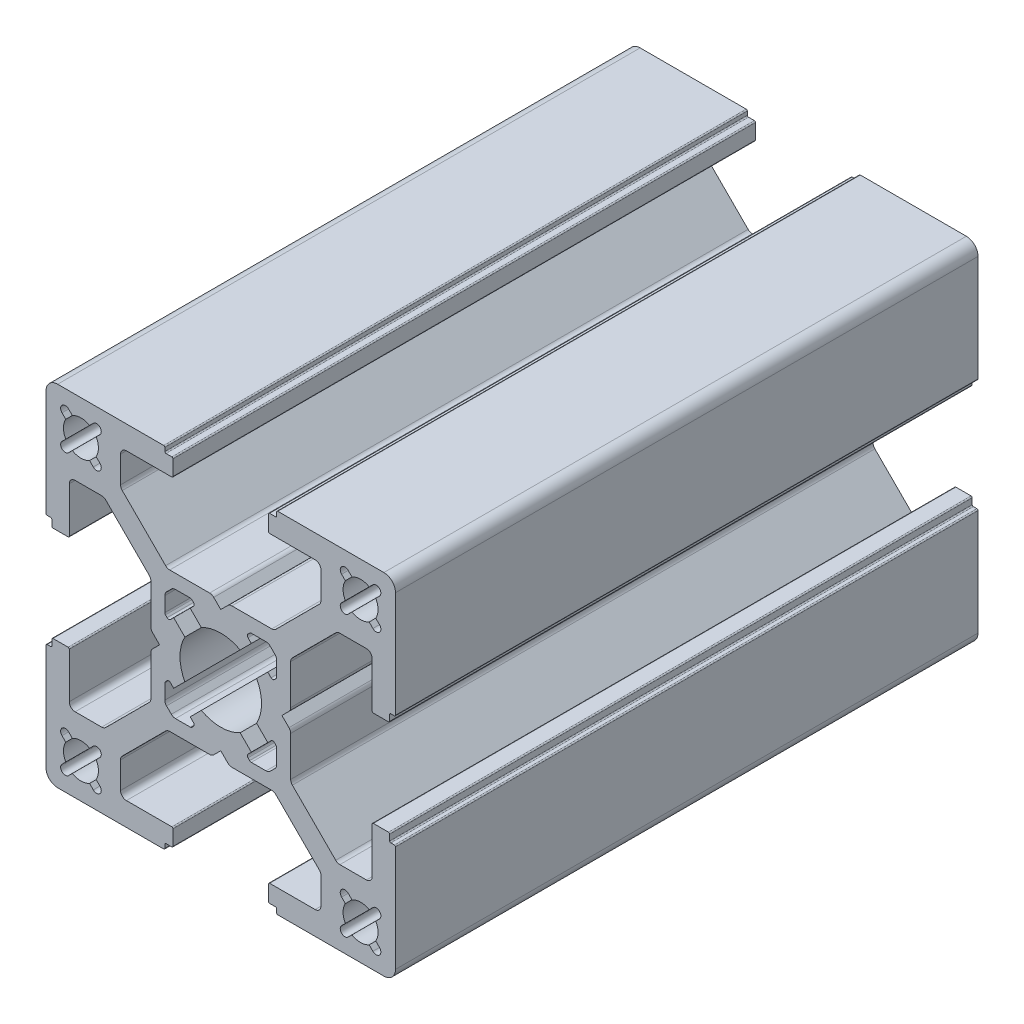
SolidWorks part; units mm, degrees
material "6061 Alaşım"
ref_plane "Ön Düzlem" through (0, 0, 0) normal (0, 0, 1) x (1, 0, 0)
ref_plane "Üst Düzlem" through (0, 0, 0) normal (0, 1, 0) x (1, 0, 0)
ref_plane "Sağ Düzlem" through (0, 0, 0) normal (1, 0, 0) x (0, 0, -1)
sketch "Çizim1" plane through (0, 0, 0) normal (0, 0, 1) x (1, 0, 0)
  line L0 (-4.8, 14.9) -> (-4.8, 14.6)
  line L1 (15, -15) -> (-15, -15) construction
  line L2 (15, -15) -> (15, 15) construction
  line L3 (15, 15) -> (-15, 15) construction
  line L4 (-15, -15) -> (-15, 15) construction
  line L5 (0, 15) -> (0, -15) construction
  line L6 (15, 0) -> (-15, 0) construction
  line L7 (-4.7, 14.5) -> (-4.2, 14.5)
  line L8 (-4.1, 14.4) -> (-4.1, 13.1)
  line L9 (-4.2, 13) -> (-8.1, 13)
  line L10 (-8.6, 12.5) -> (-8.6, 10.2213)
  line L11 (-8.4536, 9.8678) -> (-4.7322, 6.1464)
  line L12 (-4.3787, 6) -> (-0.9571, 6)
  line L13 (-0.6036, 5.8536) -> (0, 5.25)
  line L14 (-15, 15) -> (0, 0) construction
  line L15 (-4.9, 15) -> (-14, 15)
  line L16 (-4.5858, 6) -> (-1.6646, 3.0788) construction
  line L17 (-4.6536, 4.2393) -> (-4.2393, 4.6536)
  line L18 (-3.8858, 4.8) -> (-2.6201, 4.8)
  line L19 (-2.4787, 4.7414) -> (-2.3414, 4.6042)
  line L20 (-2.3414, 4.3213) -> (-2.6243, 4.0385)
  line L21 (-2.6243, 4.0385) -> (-1.6646, 3.0788)
  line L22 (0, 5.25) -> (0, 3.5)
  line L23 (-13.0607, 10.9393) -> (-10.9393, 13.0607) construction
  line L24 (-10.9393, 13.0607) -> (-10.6565, 13.3435) construction
  line L25 (-11.2606, 13.3051) -> (-10.9393, 13.6263)
  line L26 (-10.6949, 12.7394) -> (-10.3737, 13.0607)
  line L27 (-10.3737, 10.9393) -> (-10.6949, 11.2606)
  line L28 (-10.9393, 13.6263) -> (-10.3737, 13.0607) construction
  line L29 (-10.6565, 10.6565) -> (-10.3737, 10.9393) construction
  line L31 (-10.3737, 10.3737) -> (-4.4464, 4.4464) construction
  line L32 (-10.9393, 10.3737) -> (-11.2606, 10.6949)
  line L33 (-12.7394, 10.6949) -> (-13.0607, 10.3737)
  line L34 (-13.3051, 11.2606) -> (-13.6263, 10.9393)
  line L35 (-15, 4.9) -> (-15, 14)
  line L36 (-14.9, 4.8) -> (-14.6, 4.8)
  line L37 (-14.5, 4.7) -> (-14.5, 4.2)
  line L38 (-14.4, 4.1) -> (-13.1, 4.1)
  line L39 (-13, 4.2) -> (-13, 8.1)
  line L40 (-12.5, 8.6) -> (-10.2213, 8.6)
  line L41 (-9.8678, 8.4536) -> (-6.1464, 4.7322)
  line L42 (-6, 4.3787) -> (-6, 0.9571)
  line L43 (-5.8536, 0.6036) -> (-5.25, 0)
  line L44 (-5.25, 0) -> (-3.5, 0)
  line L45 (-4.0385, 2.6243) -> (-3.0788, 1.6646)
  line L46 (-4.3213, 2.3414) -> (-4.0385, 2.6243)
  line L47 (-4.7414, 2.4787) -> (-4.6042, 2.3414)
  line L48 (-4.8, 3.8858) -> (-4.8, 2.6201)
  line L49 (-13.0607, 13.6263) -> (-12.7394, 13.3051)
  line L50 (-13.6263, 13.0607) -> (-13.3051, 12.7394)
  line L51 (15, 4.9) -> (15, 14)
  line L52 (14.9, 4.8) -> (14.6, 4.8)
  line L53 (14.5, 4.7) -> (14.5, 4.2)
  line L54 (14.4, 4.1) -> (13.1, 4.1)
  line L55 (13, 4.2) -> (13, 8.1)
  line L56 (12.5, 8.6) -> (10.2213, 8.6)
  line L57 (9.8678, 8.4536) -> (6.1464, 4.7322)
  line L58 (6, 4.3787) -> (6, 0.9571)
  line L59 (5.8536, 0.6036) -> (5.25, 0)
  line L60 (5.25, 0) -> (3.5, 0)
  line L61 (4.0385, 2.6243) -> (3.0788, 1.6646)
  line L62 (4.3213, 2.3414) -> (4.0385, 2.6243)
  line L63 (4.7414, 2.4787) -> (4.6042, 2.3414)
  line L64 (4.8, 3.8858) -> (4.8, 2.6201)
  line L65 (4.2393, 4.6536) -> (4.6536, 4.2393)
  line L66 (3.8858, 4.8) -> (2.6201, 4.8)
  line L67 (2.4787, 4.7414) -> (2.3414, 4.6042)
  line L68 (2.3414, 4.3213) -> (2.6243, 4.0385)
  line L69 (2.6243, 4.0385) -> (1.6646, 3.0788)
  line L70 (0, 5.25) -> (0, 3.5)
  line L71 (0.6036, 5.8536) -> (0, 5.25)
  line L72 (4.3787, 6) -> (0.9571, 6)
  line L73 (8.4536, 9.8678) -> (4.7322, 6.1464)
  line L74 (8.6, 12.5) -> (8.6, 10.2213)
  line L75 (4.2, 13) -> (8.1, 13)
  line L76 (4.1, 14.4) -> (4.1, 13.1)
  line L77 (4.7, 14.5) -> (4.2, 14.5)
  line L78 (4.8, 14.9) -> (4.8, 14.6)
  line L79 (4.9, 15) -> (14, 15)
  line L80 (13.3051, 11.2606) -> (13.6263, 10.9393)
  line L81 (12.7394, 10.6949) -> (13.0607, 10.3737)
  line L82 (10.9393, 10.3737) -> (11.2606, 10.6949)
  line L83 (10.3737, 10.9393) -> (10.6949, 11.2606)
  line L84 (10.6949, 12.7394) -> (10.3737, 13.0607)
  line L85 (11.2606, 13.3051) -> (10.9393, 13.6263)
  line L86 (13.0607, 13.6263) -> (12.7394, 13.3051)
  line L87 (13.6263, 13.0607) -> (13.3051, 12.7394)
  line L88 (4.9, -15) -> (14, -15)
  line L89 (4.8, -14.9) -> (4.8, -14.6)
  line L90 (4.7, -14.5) -> (4.2, -14.5)
  line L91 (4.1, -14.4) -> (4.1, -13.1)
  line L92 (4.2, -13) -> (8.1, -13)
  line L93 (8.6, -12.5) -> (8.6, -10.2213)
  line L94 (8.4536, -9.8678) -> (4.7322, -6.1464)
  line L95 (4.3787, -6) -> (0.9571, -6)
  line L96 (0.6036, -5.8536) -> (0, -5.25)
  line L97 (0, -5.25) -> (0, -3.5)
  line L98 (2.6243, -4.0385) -> (1.6646, -3.0788)
  line L99 (2.3414, -4.3213) -> (2.6243, -4.0385)
  line L100 (2.4787, -4.7414) -> (2.3414, -4.6042)
  line L101 (3.8858, -4.8) -> (2.6201, -4.8)
  line L102 (4.6536, -4.2393) -> (4.2393, -4.6536)
  line L103 (4.8, -3.8858) -> (4.8, -2.6201)
  line L104 (4.7414, -2.4787) -> (4.6042, -2.3414)
  line L105 (4.3213, -2.3414) -> (4.0385, -2.6243)
  line L106 (4.0385, -2.6243) -> (3.0788, -1.6646)
  line L107 (5.25, 0) -> (3.5, 0)
  line L108 (5.8536, -0.6036) -> (5.25, 0)
  line L109 (6, -4.3787) -> (6, -0.9571)
  line L110 (9.8678, -8.4536) -> (6.1464, -4.7322)
  line L111 (12.5, -8.6) -> (10.2213, -8.6)
  line L112 (13, -4.2) -> (13, -8.1)
  line L113 (14.4, -4.1) -> (13.1, -4.1)
  line L114 (14.5, -4.7) -> (14.5, -4.2)
  line L115 (14.9, -4.8) -> (14.6, -4.8)
  line L116 (15, -4.9) -> (15, -14)
  line L117 (11.2606, -13.3051) -> (10.9393, -13.6263)
  line L118 (10.6949, -12.7394) -> (10.3737, -13.0607)
  line L119 (10.3737, -10.9393) -> (10.6949, -11.2606)
  line L120 (10.9393, -10.3737) -> (11.2606, -10.6949)
  line L121 (12.7394, -10.6949) -> (13.0607, -10.3737)
  line L122 (13.3051, -11.2606) -> (13.6263, -10.9393)
  line L123 (13.6263, -13.0607) -> (13.3051, -12.7394)
  line L124 (13.0607, -13.6263) -> (12.7394, -13.3051)
  line L125 (-15, -4.9) -> (-15, -14)
  line L126 (-14.9, -4.8) -> (-14.6, -4.8)
  line L127 (-14.5, -4.7) -> (-14.5, -4.2)
  line L128 (-14.4, -4.1) -> (-13.1, -4.1)
  line L129 (-13, -4.2) -> (-13, -8.1)
  line L130 (-12.5, -8.6) -> (-10.2213, -8.6)
  line L131 (-9.8678, -8.4536) -> (-6.1464, -4.7322)
  line L132 (-6, -4.3787) -> (-6, -0.9571)
  line L133 (-5.8536, -0.6036) -> (-5.25, 0)
  line L134 (-5.25, 0) -> (-3.5, 0)
  line L135 (-4.0385, -2.6243) -> (-3.0788, -1.6646)
  line L136 (-4.3213, -2.3414) -> (-4.0385, -2.6243)
  line L137 (-4.7414, -2.4787) -> (-4.6042, -2.3414)
  line L138 (-4.8, -3.8858) -> (-4.8, -2.6201)
  line L139 (-4.2393, -4.6536) -> (-4.6536, -4.2393)
  line L140 (-3.8858, -4.8) -> (-2.6201, -4.8)
  line L141 (-2.4787, -4.7414) -> (-2.3414, -4.6042)
  line L142 (-2.3414, -4.3213) -> (-2.6243, -4.0385)
  line L143 (-2.6243, -4.0385) -> (-1.6646, -3.0788)
  line L144 (0, -5.25) -> (0, -3.5)
  line L145 (-0.6036, -5.8536) -> (0, -5.25)
  line L146 (-4.3787, -6) -> (-0.9571, -6)
  line L147 (-8.4536, -9.8678) -> (-4.7322, -6.1464)
  line L148 (-8.6, -12.5) -> (-8.6, -10.2213)
  line L149 (-4.2, -13) -> (-8.1, -13)
  line L150 (-4.1, -14.4) -> (-4.1, -13.1)
  line L151 (-4.7, -14.5) -> (-4.2, -14.5)
  line L152 (-4.8, -14.9) -> (-4.8, -14.6)
  line L153 (-4.9, -15) -> (-14, -15)
  line L154 (-13.3051, -11.2606) -> (-13.6263, -10.9393)
  line L155 (-12.7394, -10.6949) -> (-13.0607, -10.3737)
  line L156 (-10.9393, -10.3737) -> (-11.2606, -10.6949)
  line L157 (-10.3737, -10.9393) -> (-10.6949, -11.2606)
  line L158 (-10.6949, -12.7394) -> (-10.3737, -13.0607)
  line L159 (-11.2606, -13.3051) -> (-10.9393, -13.6263)
  line L160 (-13.0607, -13.6263) -> (-12.7394, -13.3051)
  line L161 (-13.6263, -13.0607) -> (-13.3051, -12.7394)
  circle A0 centre (-12, 12) radius 1.5 construction
  circle A1 centre (0, 0) radius 3.5 construction
  arc A2 (-1.6646, 3.0788) -> (0, 3.5) centre (0, 0) cw
  circle A3 centre (-10.6565, 10.6565) radius 0.4 construction
  circle A4 centre (-10.6565, 13.3435) radius 0.4 construction
  arc A5 (-10.9393, 13.6263) -> (-10.3737, 13.0607) centre (-10.6565, 13.3435) cw
  arc A6 (-13.3051, 11.2606) -> (-13.3051, 12.7394) centre (-12, 12) cw
  arc A7 (-10.6949, 12.7394) -> (-10.6949, 11.2606) centre (-12, 12) cw
  arc A8 (-10.3737, 10.9393) -> (-10.9393, 10.3737) centre (-10.6565, 10.6565) cw
  arc A9 (-4.1, 13.1) -> (-4.2, 13) centre (-4.2, 13.1) cw
  arc A10 (-4.2, 14.5) -> (-4.1, 14.4) centre (-4.2, 14.4) cw
  arc A11 (-4.8, 14.6) -> (-4.7, 14.5) centre (-4.7, 14.6) ccw
  arc A12 (-4.8, 14.9) -> (-4.9, 15) centre (-4.9, 14.9) ccw
  arc A13 (-4.2393, 4.6536) -> (-3.8858, 4.8) centre (-3.8858, 4.3) cw
  arc A14 (-0.9571, 6) -> (-0.6036, 5.8536) centre (-0.9571, 5.5) cw
  arc A15 (-4.7322, 6.1464) -> (-4.3787, 6) centre (-4.3787, 6.5) ccw
  arc A16 (-8.6, 10.2213) -> (-8.4536, 9.8678) centre (-8.1, 10.2213) ccw
  arc A17 (-8.1, 13) -> (-8.6, 12.5) centre (-8.1, 12.5) ccw
  arc A18 (-2.3414, 4.6042) -> (-2.3414, 4.3213) centre (-2.4828, 4.4627) cw
  arc A19 (-2.6201, 4.8) -> (-2.4787, 4.7414) centre (-2.6201, 4.6) cw
  arc A20 (-12.7394, 10.6949) -> (-11.2606, 10.6949) centre (-12, 12) ccw
  arc A21 (-13.6263, 10.9393) -> (-13.0607, 10.3737) centre (-13.3435, 10.6565) ccw
  arc A22 (-14.9, 4.8) -> (-15, 4.9) centre (-14.9, 4.9) cw
  arc A23 (-14.6, 4.8) -> (-14.5, 4.7) centre (-14.6, 4.7) cw
  arc A24 (-14.5, 4.2) -> (-14.4, 4.1) centre (-14.4, 4.2) ccw
  arc A25 (-13.1, 4.1) -> (-13, 4.2) centre (-13.1, 4.2) ccw
  arc A26 (-13, 8.1) -> (-12.5, 8.6) centre (-12.5, 8.1) cw
  arc A27 (-10.2213, 8.6) -> (-9.8678, 8.4536) centre (-10.2213, 8.1) cw
  arc A28 (-6.1464, 4.7322) -> (-6, 4.3787) centre (-6.5, 4.3787) cw
  arc A29 (-6, 0.9571) -> (-5.8536, 0.6036) centre (-5.5, 0.9571) ccw
  arc A30 (-3.0788, 1.6646) -> (-3.5, 0) centre (0, 0) ccw
  arc A31 (-4.6042, 2.3414) -> (-4.3213, 2.3414) centre (-4.4627, 2.4828) ccw
  arc A32 (-4.8, 2.6201) -> (-4.7414, 2.4787) centre (-4.6, 2.6201) ccw
  arc A33 (-4.6536, 4.2393) -> (-4.8, 3.8858) centre (-4.3, 3.8858) ccw
  arc A34 (-15, 14) -> (-14, 15) centre (-14, 14) cw
  arc A35 (-13.0607, 13.6263) -> (-13.6263, 13.0607) centre (-13.3435, 13.3435) ccw
  arc A36 (-12.7394, 13.3051) -> (-11.2606, 13.3051) centre (-12, 12) cw
  arc A37 (13.3051, 12.7394) -> (13.3051, 11.2606) centre (12, 12) cw
  arc A38 (14, 15) -> (15, 14) centre (14, 14) cw
  arc A39 (14.9, 4.8) -> (15, 4.9) centre (14.9, 4.9) ccw
  arc A40 (14.6, 4.8) -> (14.5, 4.7) centre (14.6, 4.7) ccw
  arc A41 (14.5, 4.2) -> (14.4, 4.1) centre (14.4, 4.2) cw
  arc A42 (13.1, 4.1) -> (13, 4.2) centre (13.1, 4.2) cw
  arc A43 (13, 8.1) -> (12.5, 8.6) centre (12.5, 8.1) ccw
  arc A44 (10.2213, 8.6) -> (9.8678, 8.4536) centre (10.2213, 8.1) ccw
  arc A45 (6.1464, 4.7322) -> (6, 4.3787) centre (6.5, 4.3787) ccw
  arc A46 (6, 0.9571) -> (5.8536, 0.6036) centre (5.5, 0.9571) cw
  arc A47 (3.0788, 1.6646) -> (3.5, 0) centre (0, 0) cw
  arc A48 (4.6042, 2.3414) -> (4.3213, 2.3414) centre (4.4627, 2.4828) cw
  arc A49 (4.8, 2.6201) -> (4.7414, 2.4787) centre (4.6, 2.6201) cw
  arc A50 (4.6536, 4.2393) -> (4.8, 3.8858) centre (4.3, 3.8858) cw
  arc A51 (4.2393, 4.6536) -> (3.8858, 4.8) centre (3.8858, 4.3) ccw
  arc A52 (2.6201, 4.8) -> (2.4787, 4.7414) centre (2.6201, 4.6) ccw
  arc A53 (2.3414, 4.6042) -> (2.3414, 4.3213) centre (2.4828, 4.4627) ccw
  arc A54 (1.6646, 3.0788) -> (0, 3.5) centre (0, 0) ccw
  arc A55 (0.9571, 6) -> (0.6036, 5.8536) centre (0.9571, 5.5) ccw
  arc A56 (4.7322, 6.1464) -> (4.3787, 6) centre (4.3787, 6.5) cw
  arc A57 (8.6, 10.2213) -> (8.4536, 9.8678) centre (8.1, 10.2213) cw
  arc A58 (8.1, 13) -> (8.6, 12.5) centre (8.1, 12.5) cw
  arc A59 (4.1, 13.1) -> (4.2, 13) centre (4.2, 13.1) ccw
  arc A60 (4.2, 14.5) -> (4.1, 14.4) centre (4.2, 14.4) ccw
  arc A61 (4.8, 14.6) -> (4.7, 14.5) centre (4.7, 14.6) cw
  arc A62 (4.8, 14.9) -> (4.9, 15) centre (4.9, 14.9) cw
  arc A63 (13.6263, 10.9393) -> (13.0607, 10.3737) centre (13.3435, 10.6565) cw
  arc A64 (12.7394, 10.6949) -> (11.2606, 10.6949) centre (12, 12) cw
  arc A65 (10.9393, 10.3737) -> (10.3737, 10.9393) centre (10.6565, 10.6565) cw
  arc A66 (10.6949, 12.7394) -> (10.6949, 11.2606) centre (12, 12) ccw
  arc A67 (10.9393, 13.6263) -> (10.3737, 13.0607) centre (10.6565, 13.3435) ccw
  arc A68 (11.2606, 13.3051) -> (12.7394, 13.3051) centre (12, 12) cw
  arc A69 (13.6263, 13.0607) -> (13.0607, 13.6263) centre (13.3435, 13.3435) ccw
  arc A70 (12.7394, -13.3051) -> (11.2606, -13.3051) centre (12, -12) cw
  arc A71 (15, -14) -> (14, -15) centre (14, -14) cw
  arc A72 (4.8, -14.9) -> (4.9, -15) centre (4.9, -14.9) ccw
  arc A73 (4.8, -14.6) -> (4.7, -14.5) centre (4.7, -14.6) ccw
  arc A74 (4.2, -14.5) -> (4.1, -14.4) centre (4.2, -14.4) cw
  arc A75 (4.1, -13.1) -> (4.2, -13) centre (4.2, -13.1) cw
  arc A76 (8.1, -13) -> (8.6, -12.5) centre (8.1, -12.5) ccw
  arc A77 (8.6, -10.2213) -> (8.4536, -9.8678) centre (8.1, -10.2213) ccw
  arc A78 (4.7322, -6.1464) -> (4.3787, -6) centre (4.3787, -6.5) ccw
  arc A79 (0.9571, -6) -> (0.6036, -5.8536) centre (0.9571, -5.5) cw
  arc A80 (1.6646, -3.0788) -> (0, -3.5) centre (0, 0) cw
  arc A81 (2.3414, -4.6042) -> (2.3414, -4.3213) centre (2.4828, -4.4627) cw
  arc A82 (2.6201, -4.8) -> (2.4787, -4.7414) centre (2.6201, -4.6) cw
  arc A83 (4.2393, -4.6536) -> (3.8858, -4.8) centre (3.8858, -4.3) cw
  arc A84 (4.6536, -4.2393) -> (4.8, -3.8858) centre (4.3, -3.8858) ccw
  arc A85 (4.8, -2.6201) -> (4.7414, -2.4787) centre (4.6, -2.6201) ccw
  arc A86 (4.6042, -2.3414) -> (4.3213, -2.3414) centre (4.4627, -2.4828) ccw
  arc A87 (3.0788, -1.6646) -> (3.5, 0) centre (0, 0) ccw
  arc A88 (6, -0.9571) -> (5.8536, -0.6036) centre (5.5, -0.9571) ccw
  arc A89 (6.1464, -4.7322) -> (6, -4.3787) centre (6.5, -4.3787) cw
  arc A90 (10.2213, -8.6) -> (9.8678, -8.4536) centre (10.2213, -8.1) cw
  arc A91 (13, -8.1) -> (12.5, -8.6) centre (12.5, -8.1) cw
  arc A92 (13.1, -4.1) -> (13, -4.2) centre (13.1, -4.2) ccw
  arc A93 (14.5, -4.2) -> (14.4, -4.1) centre (14.4, -4.2) ccw
  arc A94 (14.6, -4.8) -> (14.5, -4.7) centre (14.6, -4.7) cw
  arc A95 (14.9, -4.8) -> (15, -4.9) centre (14.9, -4.9) cw
  arc A96 (10.9393, -13.6263) -> (10.3737, -13.0607) centre (10.6565, -13.3435) cw
  arc A97 (10.6949, -12.7394) -> (10.6949, -11.2606) centre (12, -12) cw
  arc A98 (10.3737, -10.9393) -> (10.9393, -10.3737) centre (10.6565, -10.6565) cw
  arc A99 (12.7394, -10.6949) -> (11.2606, -10.6949) centre (12, -12) ccw
  arc A100 (13.6263, -10.9393) -> (13.0607, -10.3737) centre (13.3435, -10.6565) ccw
  arc A101 (13.3051, -11.2606) -> (13.3051, -12.7394) centre (12, -12) cw
  arc A102 (13.0607, -13.6263) -> (13.6263, -13.0607) centre (13.3435, -13.3435) ccw
  arc A103 (-13.3051, -12.7394) -> (-13.3051, -11.2606) centre (-12, -12) cw
  arc A104 (-14, -15) -> (-15, -14) centre (-14, -14) cw
  arc A105 (-14.9, -4.8) -> (-15, -4.9) centre (-14.9, -4.9) ccw
  arc A106 (-14.6, -4.8) -> (-14.5, -4.7) centre (-14.6, -4.7) ccw
  arc A107 (-14.5, -4.2) -> (-14.4, -4.1) centre (-14.4, -4.2) cw
  arc A108 (-13.1, -4.1) -> (-13, -4.2) centre (-13.1, -4.2) cw
  arc A109 (-13, -8.1) -> (-12.5, -8.6) centre (-12.5, -8.1) ccw
  arc A110 (-10.2213, -8.6) -> (-9.8678, -8.4536) centre (-10.2213, -8.1) ccw
  arc A111 (-6.1464, -4.7322) -> (-6, -4.3787) centre (-6.5, -4.3787) ccw
  arc A112 (-6, -0.9571) -> (-5.8536, -0.6036) centre (-5.5, -0.9571) cw
  arc A113 (-3.0788, -1.6646) -> (-3.5, 0) centre (0, 0) cw
  arc A114 (-4.6042, -2.3414) -> (-4.3213, -2.3414) centre (-4.4627, -2.4828) cw
  arc A115 (-4.8, -2.6201) -> (-4.7414, -2.4787) centre (-4.6, -2.6201) cw
  arc A116 (-4.6536, -4.2393) -> (-4.8, -3.8858) centre (-4.3, -3.8858) cw
  arc A117 (-4.2393, -4.6536) -> (-3.8858, -4.8) centre (-3.8858, -4.3) ccw
  arc A118 (-2.6201, -4.8) -> (-2.4787, -4.7414) centre (-2.6201, -4.6) ccw
  arc A119 (-2.3414, -4.6042) -> (-2.3414, -4.3213) centre (-2.4828, -4.4627) ccw
  arc A120 (-1.6646, -3.0788) -> (0, -3.5) centre (0, 0) ccw
  arc A121 (-0.9571, -6) -> (-0.6036, -5.8536) centre (-0.9571, -5.5) ccw
  arc A122 (-4.7322, -6.1464) -> (-4.3787, -6) centre (-4.3787, -6.5) cw
  arc A123 (-8.6, -10.2213) -> (-8.4536, -9.8678) centre (-8.1, -10.2213) cw
  arc A124 (-8.1, -13) -> (-8.6, -12.5) centre (-8.1, -12.5) cw
  arc A125 (-4.1, -13.1) -> (-4.2, -13) centre (-4.2, -13.1) ccw
  arc A126 (-4.2, -14.5) -> (-4.1, -14.4) centre (-4.2, -14.4) ccw
  arc A127 (-4.8, -14.6) -> (-4.7, -14.5) centre (-4.7, -14.6) cw
  arc A128 (-4.8, -14.9) -> (-4.9, -15) centre (-4.9, -14.9) cw
  arc A129 (-13.6263, -10.9393) -> (-13.0607, -10.3737) centre (-13.3435, -10.6565) cw
  arc A130 (-12.7394, -10.6949) -> (-11.2606, -10.6949) centre (-12, -12) cw
  arc A131 (-10.9393, -10.3737) -> (-10.3737, -10.9393) centre (-10.6565, -10.6565) cw
  arc A132 (-10.6949, -12.7394) -> (-10.6949, -11.2606) centre (-12, -12) ccw
  arc A133 (-10.9393, -13.6263) -> (-10.3737, -13.0607) centre (-10.6565, -13.3435) ccw
  arc A134 (-11.2606, -13.3051) -> (-12.7394, -13.3051) centre (-12, -12) cw
  arc A135 (-13.6263, -13.0607) -> (-13.0607, -13.6263) centre (-13.3435, -13.3435) ccw
  point P0 (0, 0)
  point P27 (-12, 12)
  point P38 (-10.6565, 13.3435)
  point P49 (-4.1, 14.5)
  point P52 (-4.8, 14.5)
  point P55 (-4.8, 15)
  point P58 (-4.0929, 4.8)
  point P61 (-0.75, 6)
  point P71 (-2.2, 4.4627)
  point P435 (0, 0)
  dimension "D8" = 3
  dimension "D13" = 7
  dimension "D18" = 0.8
  dimension "D19" = 0.8
  dimension "D20" = 0.1
  dimension "D21" = 0.5
  dimension "D22" = 0.2
  dimension "D23" = 1
  dimension "D1" = 30
  dimension "D2" = 30
  dimension "D3" = 2
  dimension "D4" = 0.5
  dimension "D5" = 0.7
  dimension "D6" = 8.2
  dimension "D7" = 2
  dimension "D9" = 6
  dimension "D10" = 0.75
  dimension "D11" = 4.5
  dimension "D12" = 3
  dimension "D14" = 0.6
  dimension "D15" = 0.5
  dimension "D16" = 1.2
  dimension "D17" = 2.2
  dimension "D24" = 4
extrude "Yükseklik-Ekstrüzyon1" add sketch "Çizim1" against normal blind 50 contours A34 L35 A22 L36 A23 L37 A24 L38 A25 L39 A26 L40 A27 L41 A28 L42 A29 L43 L44 A30 L45 L46 A31 L47 A32 L48 A33 L17 A13 L18 A19 L19 A18 L20 L21 A2 L22 L13 A14 L12 A15 L11 A16 L10 A17 L9 A9 L8 A10 L7 A11 | A62 L78 A61 L77 A60 L76 A59 L75 A58 L74 A57 L73 A56 L72 A55 L71 L22 A54 L69 L68 A53 L67 A52 L66 A51 L65 A50 L64 A49 L63 A48 L62 L61 A47 L60 L59 A46 L58 A45 L57 A44 L56 A43 L55 A42 L54 A41 L53 A40 L52 A39 | A95 L115 A94 L114 A93 L113 A92 L112 A91 L111 A90 L110 A89 L109 A88 L108 L60 A87 L106 L105 A86 L104 A85 L103 A84 L102 A83 L101 A82 L100 A81 L99 L98 A80 L97 L96 A79 L95 A78 L94 A77 L93 A76 L92 A75 L91 A74 L90 A73 L89 A72 | A128 L152 A127 L151 A126 L150 A125 L149 A124 L148 A123 L147 A122 L146 A121 L145 L97 A120 L143 L142 A119 L141 A118 L140 A117 L139 A116 L138 A115 L137 A114 L136 L135 A113 L44 L133 A112 L132 A111 L131 A110 L130 A109 L129 A108 L128 A107 L127 A106 L126 A105
